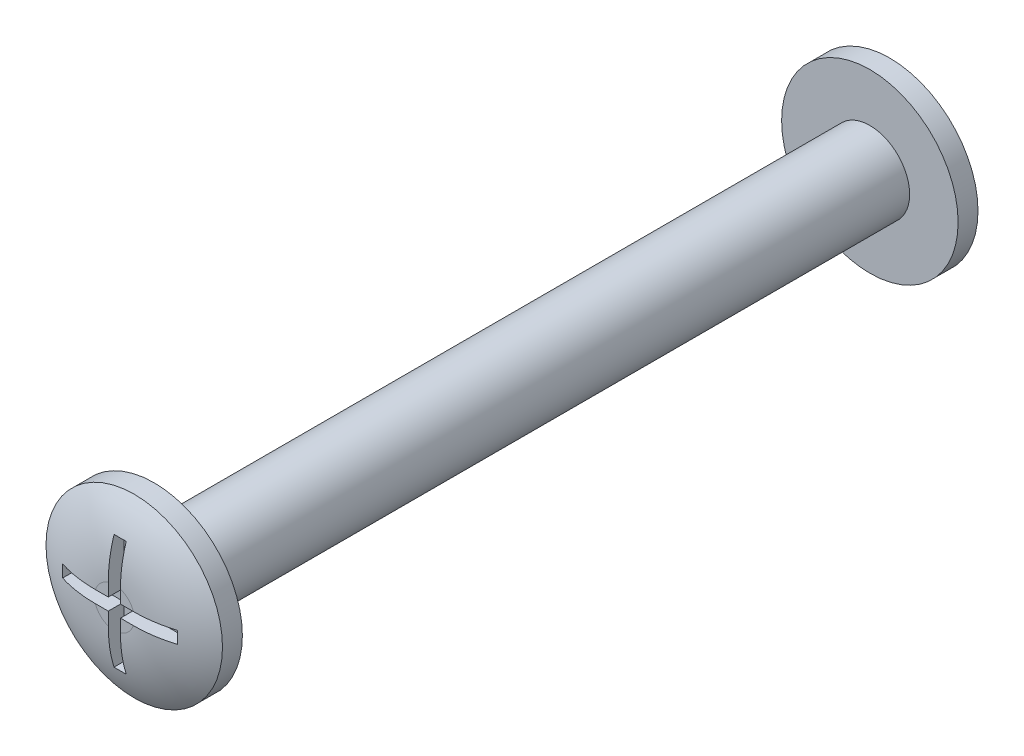
SolidWorks part; units mm, degrees
ref_plane "Front Plane" through (0, 0, 0) normal (0, 0, 1) x (1, 0, 0)
ref_plane "Top Plane" through (0, 0, 0) normal (0, 1, 0) x (1, 0, 0)
ref_plane "Right Plane" through (0, 0, 0) normal (1, 0, 0) x (0, 0, -1)
sketch "Sketch1" plane through (0, 0, 0) normal (0, 1, 0) x (1, 0, 0)
  line L0 (0, 0) -> (0, -3.175)
  line L1 (0, 57.15) -> (0, 60.325)
  line L2 (0, 0) -> (0, 57.15)
  line L3 (0, 57.15) -> (3.175, 57.15) construction
  line L4 (3.175, 57.15) -> (3.175, 0)
  line L5 (3.175, 0) -> (0, 0) construction
  line L6 (3.175, 0) -> (7.0459, 0)
  line L7 (3.175, 57.15) -> (7.0459, 57.15)
  line L8 (7.0459, 0) -> (7.0459, -1.5875)
  line L9 (0, -3.175) -> (1.5875, -3.175)
  line L12 (7.0459, 57.15) -> (7.0459, 58.7375)
  line L13 (0, 60.325) -> (1.5875, 60.325)
  arc A0 (7.0459, -1.5875) -> (1.5875, -3.175) centre (1.5875, 7.0027) cw
  arc A1 (1.5875, 60.325) -> (7.0459, 58.7375) centre (1.5875, 50.1473) cw
  dimension "D1" = 57.15
  dimension "D2" = 7.0459
  dimension "D3" = 1.5875
  dimension "D4" = 3.175
revolve "Revolve1" add sketch "Sketch1" angle 360 about L2
sketch "Sketch2" plane through (0, 0, 3.175) normal (0, 0, 1) x (1, 0, 0)
  line L1 (4.5932, -0.4856) -> (-4.5932, -0.4856)
  line L2 (4.5932, -0.4856) -> (4.5932, 0.4856)
  line L3 (4.5932, 0.4856) -> (-4.5932, 0.4856)
  line L4 (-4.5932, -0.4856) -> (-4.5932, 0.4856)
  line L5 (4.5932, -0.4856) -> (-4.5932, 0.4856) construction
  line L6 (4.5932, 0.4856) -> (-4.5932, -0.4856) construction
  line L7 (0.4856, 4.5932) -> (-0.4856, 4.5932)
  line L8 (0.4856, 4.5932) -> (0.4856, -4.5932)
  line L9 (0.4856, -4.5932) -> (-0.4856, -4.5932)
  line L10 (-0.4856, 4.5932) -> (-0.4856, -4.5932)
  line L11 (0.4856, 4.5932) -> (-0.4856, -4.5932) construction
  line L12 (0.4856, -4.5932) -> (-0.4856, 4.5932) construction
  point P0 (0, 0)
  point P6 (0, 0)
extrude "Cut-Extrude1" cut sketch "Sketch2" against normal blind 1.27 contours L3 L4 L1 L2 | L10 L9 L8 L7
ref_plane "Plane1" through (0, 0, -28.575) normal (0, 0, -1) x (-1, 0, 0)
mirror "Mirror1" about plane through (0, 0, -28.575) normal (0, 0, -1) of "Cut-Extrude1"
